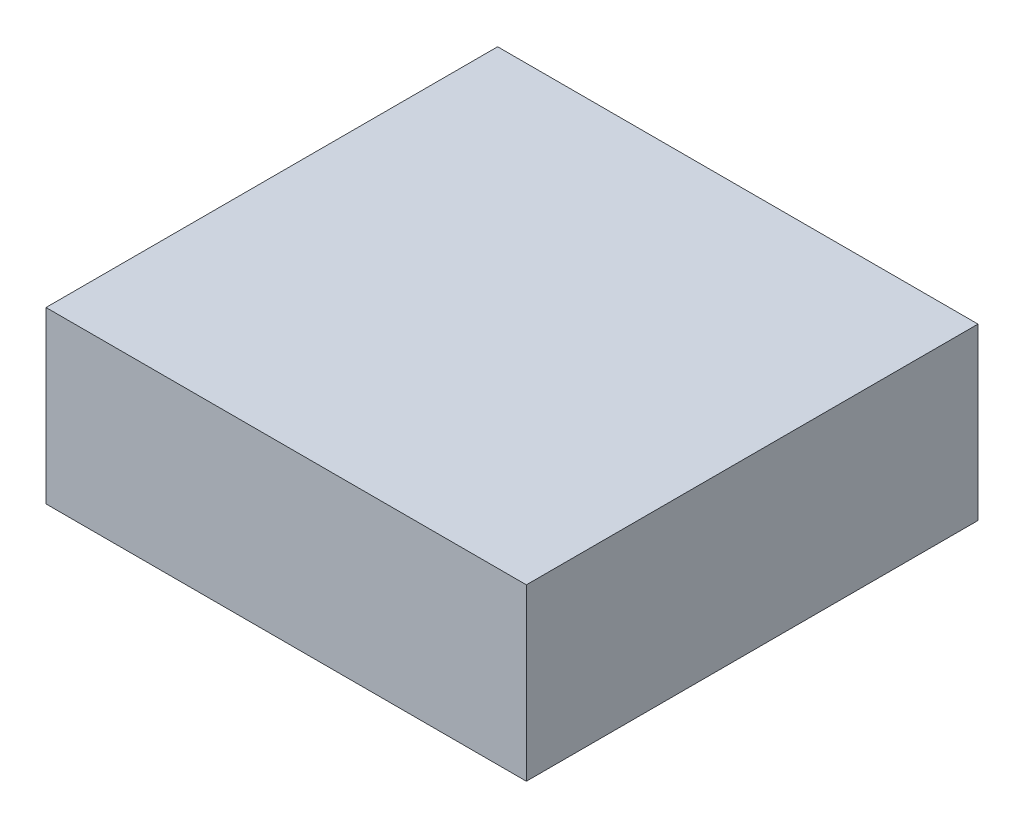
SolidWorks part; units mm, degrees
ref_plane "Front Plane" through (0, 0, 0) normal (0, 0, 1) x (1, 0, 0)
ref_plane "Top Plane" through (0, 0, 0) normal (0, 1, 0) x (1, 0, 0)
ref_plane "Right Plane" through (0, 0, 0) normal (1, 0, 0) x (0, 0, -1)
sketch "Sketch1" plane through (0, 0, 0) normal (0, 0, 1) x (1, 0, 0)
  line L1 (-53.1816, -18.8343) -> (53.1816, -18.8343)
  line L2 (-53.1816, -18.8343) -> (-53.1816, 18.8343)
  line L3 (-53.1816, 18.8343) -> (53.1816, 18.8343)
  line L4 (53.1816, -18.8343) -> (53.1816, 18.8343)
  line L5 (-53.1816, -18.8343) -> (53.1816, 18.8343) construction
  line L6 (-53.1816, 18.8343) -> (53.1816, -18.8343) construction
  point P0 (0, 0)
  point P5 (0, 0)
  point P6 (0, 0)
extrude "Boss-Extrude1" add sketch "Sketch1" against normal mid plane 100
